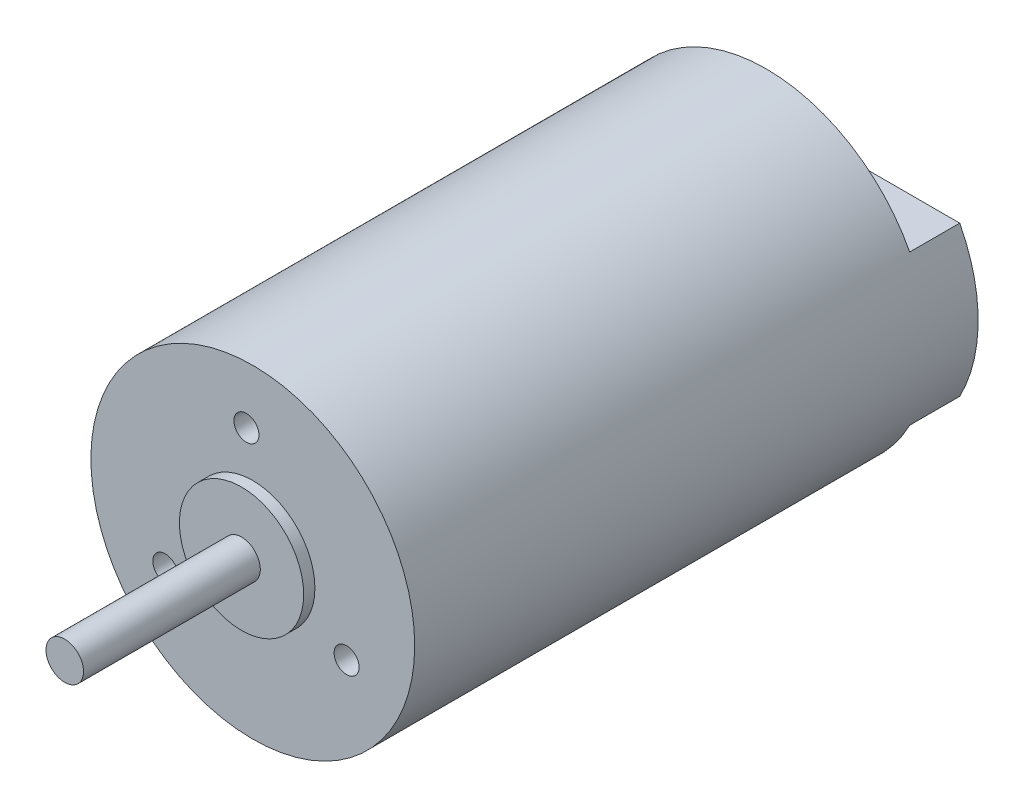
SolidWorks part; units mm, degrees
ref_plane "Front Plane" through (0, 0, 0) normal (0, 0, 1) x (1, 0, 0)
ref_plane "Top Plane" through (0, 0, 0) normal (0, 1, 0) x (1, 0, 0)
ref_plane "Right Plane" through (0, 0, 0) normal (1, 0, 0) x (0, 0, -1)
sketch "Sketch1" plane through (0, 0, 0) normal (0, 0, 1) x (1, 0, 0)
  circle A0 centre (0, 0) radius 12.95
  dimension "D1" = 25.9
extrude "Boss-Extrude1" add sketch "Sketch1" along normal blind 41.07
sketch "Sketch2" plane through (0, 0, 41.07) normal (0, 0, 1) x (1, 0, 0)
  circle A0 centre (0, 0) radius 4.97
  dimension "D1" = 9.94
extrude "Boss-Extrude2" add sketch "Sketch2" along normal blind 0.9
sketch "Sketch3" plane through (0, 0, 41.97) normal (0, 0, 1) x (1, 0, 0)
  circle A0 centre (0, 0) radius 1.5
  dimension "D1" = 3
extrude "Boss-Extrude3" add sketch "Sketch3" along normal blind 14.14
hole_wizard "Ø2.0 (2) Diameter Hole1" positions "Sketch5" profile "Sketch4" hole size "Ø2.0" standard "ISO"
sketch "Sketch5" plane through (0, 0, 41.07) normal (0, 0, 1) x (1, 0, 0)
  circle A0 centre (0, 0) radius 8.3767
  point P0 (-0.5081, 8.3613)
  point P2 (7.5031, -3.7247)
  point P4 (-6.9969, -4.6058)
  dimension "D1" = 14.5
  dimension "D2" = 14.5
  dimension "D3" = 14.5
sketch "Sketch4" plane through (-0.5081, 8.3613, 41.07) normal (1, 0, 0) x (0, -1, 0)
  line L0 (0, 0) -> (0, 5.6009)
  line L1 (0, 5.6009) -> (1, 5)
  line L2 (1, 5) -> (1, 0)
  line L5 (1, 0) -> (0, 0)
  line L10 (0, 5.6009) -> (-1, 5) construction
  line L11 (0, -6.35) -> (0, 107.95) construction
  dimension "Hole Dia." = 2
  dimension "Hole Depth" = 5
  dimension "Drill Angle" = 118
sketch "Sketch6" plane through (0, 0, 0) normal (0, 0, -1) x (-1, 0, 0)
  line L1 (-11.4762, -6) -> (11.4762, -6)
  line L2 (-11.4762, 6) -> (11.4762, 6)
  circle A1 centre (0, 0) radius 12.95
  circle M1 centre (0, 0) radius 12.95
  dimension "D1" = 12
  dimension "D2" = 6
extrude "Boss-Extrude4" add sketch "Sketch6" along normal blind 4 contours L2 L1 M1
